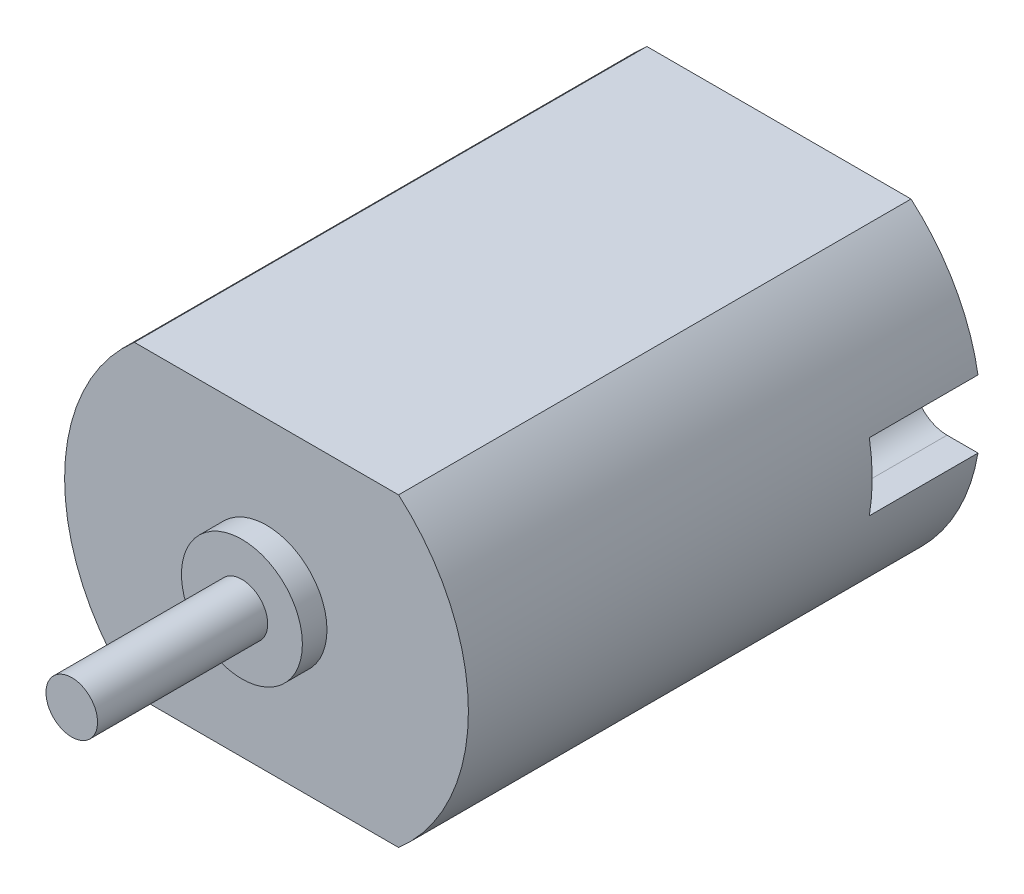
SolidWorks part; units mm, degrees
ref_plane "Alzado" through (0, 0, 0) normal (0, 0, 1) x (1, 0, 0)
ref_plane "Planta" through (0, 0, 0) normal (0, 1, 0) x (1, 0, 0)
ref_plane "Vista lateral" through (0, 0, 0) normal (1, 0, 0) x (0, 0, -1)
sketch "Croquis1" plane through (0, 0, 0) normal (0, 0, 1) x (1, 0, 0)
  line L2 (0, 7.45) -> (-6.4436, 7.45)
  line L3 (-6.4436, 7.45) -> (6.4436, 7.45)
  line L4 (0, -7.45) -> (-6.4436, -7.45)
  line L5 (-6.4436, -7.45) -> (6.4436, -7.45)
  line L6 (6.4436, 7.45) -> (0, 7.45)
  line L7 (6.4436, -7.45) -> (0, -7.45)
  arc A0 (6.4436, -7.45) -> (6.4436, 7.45) centre (0, 0) ccw
  arc A1 (-6.4436, 7.45) -> (-6.4436, -7.45) centre (0, 0) ccw
  dimension "D1" = 19.7
  dimension "D2" = 7.45
  dimension "D3" = 14.9
extrude "Saliente-Extruir1" add sketch "Croquis1" along normal blind 25 contours L2 A1 L4 L5 A0 L3
sketch "Croquis2" plane through (0, 0, 25) normal (0, 0, 1) x (1, 0, 0)
  circle A0 centre (0, 0) radius 2.95
  dimension "D1" = 5.9
extrude "Saliente-Extruir2" add sketch "Croquis2" along normal blind 1.2
sketch "Croquis3" plane through (0, 0, 0) normal (0, 0, -1) x (-1, 0, 0)
  line L0 (0, 0) -> (-9.85, 0) construction
  line L1 (-9.85, 0) -> (9.85, 0) construction
  line L2 (-8.2, 1.65) -> (-9.7108, 1.65)
  line L4 (-9.7108, -1.65) -> (-8.2, -1.65)
  line L6 (9.7108, 1.65) -> (8.2, 1.65)
  line L7 (8.2, -1.65) -> (9.7108, -1.65)
  arc A0 (-6.4436, 7.45) -> (-6.4436, -7.45) centre (0, 0) ccw construction
  arc A1 (6.4436, -7.45) -> (6.4436, 7.45) centre (0, 0) ccw construction
  arc A2 (8.2, 1.65) -> (8.2, -1.65) centre (8.2, 0) ccw
  arc A3 (-8.2, -1.65) -> (-8.2, 1.65) centre (-8.2, 0) ccw
  arc A4 (-9.7108, 1.65) -> (-9.7108, -1.65) centre (0, 0) ccw
  arc A5 (9.7108, -1.65) -> (9.7108, 1.65) centre (0, 0) ccw
  dimension "D1" = 3.3
extrude "Cortar-Extruir1" cut sketch "Croquis3" against normal blind 5.3
sketch "Croquis4" plane through (0, 0, 0) normal (0, 0, -1) x (-1, 0, 0)
  line L0 (0, 0) -> (0, 3) construction
  line L1 (0, 3) -> (-3.8743, 3)
  line L2 (-3.8743, 3) -> (3.8743, 3)
  arc A0 (-3.8743, 3) -> (3.8743, 3) centre (0, 0) ccw
  dimension "D1" = 9.8
  dimension "D2" = 3
extrude "Saliente-Extruir3" add sketch "Croquis4" along normal blind 2.4
sketch "Croquis5" plane through (0, 0, -2.4) normal (0, 0, -1) x (-1, 0, 0)
  line L0 (0, 0) -> (0, -3) construction
  line L1 (0, -3) -> (-3, -3)
  line L2 (-3, -3) -> (-3, -1.8)
  line L3 (-3, -1.8) -> (3, -1.8)
  line L4 (3, -1.8) -> (3, -3)
  line L5 (3, -3) -> (0, -3)
  dimension "D1" = 3
  dimension "D2" = 1.2
  dimension "D3" = 3
  dimension "D4" = 6
extrude "Cortar-Extruir2" cut sketch "Croquis5" against normal blind 2.5
sketch "Croquis6" plane through (0, 0, -2.4) normal (0, 0, -1) x (-1, 0, 0)
  circle A0 centre (0, 0) radius 1.2568
extrude "Saliente-Extruir4" add sketch "Croquis6" along normal blind 1.1 separate body
sketch "Croquis7" plane through (0, 0, -3.5) normal (0, 0, -1) x (-1, 0, 0)
  circle A0 centre (0, 0) radius 1.2574
extrude "Saliente-Extruir5" add sketch "Croquis7" against normal blind 38
